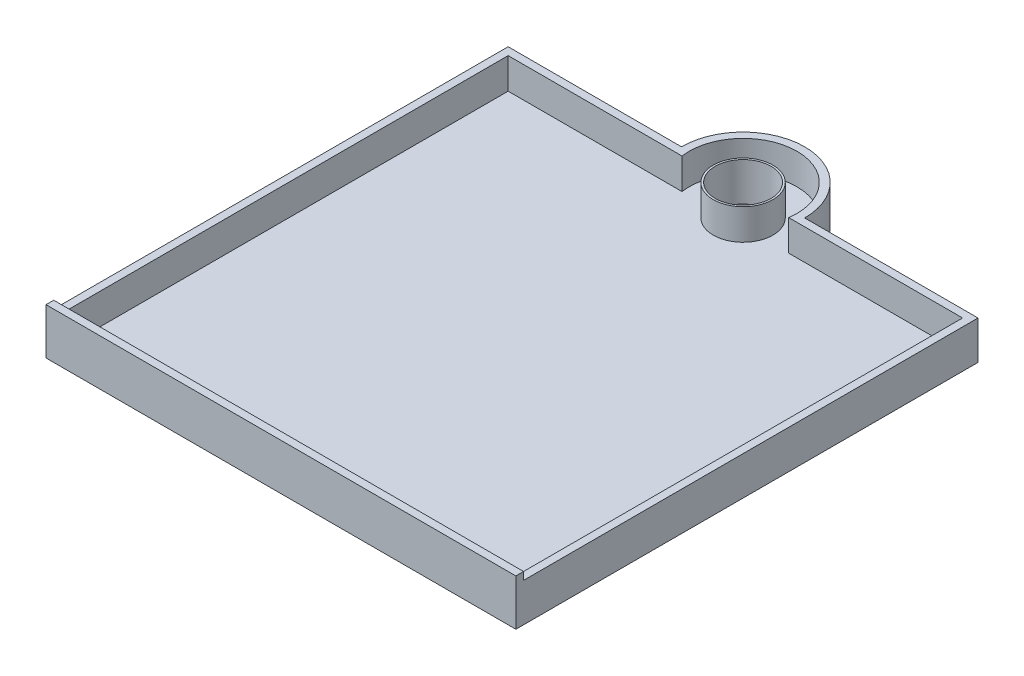
SolidWorks part; units mm, degrees
ref_plane "Front Plane" through (0, 0, 0) normal (0, 0, 1) x (1, 0, 0)
ref_plane "Top Plane" through (0, 0, 0) normal (0, 1, 0) x (1, 0, 0)
ref_plane "Right Plane" through (0, 0, 0) normal (1, 0, 0) x (0, 0, -1)
sketch "Sketch7" plane through (0, 0, 0) normal (0, 1, 0) x (1, 0, 0)
  circle A0 centre (0, 0) radius 16
extrude "Boss-Extrude3" add sketch "Sketch7" along normal blind 10 contours A0
sketch "Sketch8" plane through (0, 0, 0) normal (0, 1, 0) x (1, 0, 0)
  circle A0 centre (0, 0) radius 7.25
extrude "Cut-Extrude8" cut sketch "Sketch8" along normal blind 10
sketch "Sketch9" plane through (0, 10, 0) normal (0, 1, 0) x (1, 0, 0)
  circle A0 centre (0, 0) radius 7.75
  circle A1 centre (0, 0) radius 14
extrude "Cut-Extrude9" cut sketch "Sketch9" against normal blind 8
sketch "Sketch10" plane through (0, 2, 0) normal (0, 1, 0) x (1, 0, 0)
  line L1 (16, 0) -> (61, 0)
  line L2 (61, 0) -> (61, -120)
  line L3 (61, -120) -> (-61, -120)
  line L4 (-61, -120) -> (-61, 0)
  line L5 (-61, 0) -> (-16, 0)
  circle A0 centre (0, 0) radius 16 construction
  arc A1 (-16, 0) -> (16, 0) centre (0, 0) ccw
extrude "Boss-Extrude5" add sketch "Sketch10" along normal blind 8 and the other way blind 2
sketch "Sketch11" plane through (0, 10, 0) normal (0, 1, 0) x (1, 0, 0)
  line L3 (-59, -2) -> (-59, -118)
  line L4 (-59, -118) -> (59, -118)
  line L5 (59, -118) -> (59, -2)
  line L6 (59, -2) -> (13.8564, -2)
  line L7 (-13.8564, -2) -> (-59, -2)
  arc A1 (-13.8564, -2) -> (13.8564, -2) centre (0, 0) ccw
extrude "Cut-Extrude11" cut sketch "Sketch11" against normal blind 8
sketch "Sketch12" plane through (0, 2, 0) normal (0, 1, 0) x (1, 0, 0)
  line L0 (-59, -118) -> (-61, -118)
  line L1 (-61, 0) -> (-61, -120) construction
  line L2 (-61, -118) -> (-61, -120)
  line L3 (-61, -120) -> (61, -120)
  line L4 (61, -120) -> (61, -118)
  line L5 (61, -120) -> (61, 0) construction
  line L6 (61, -118) -> (-59, -118)
extrude "Boss-Extrude6" add sketch "Sketch12" along normal blind 10
sketch "Sketch13" plane through (0, 2, 0) normal (0, 1, 0) x (1, 0, 0)
  circle A0 centre (0, 0) radius 7
